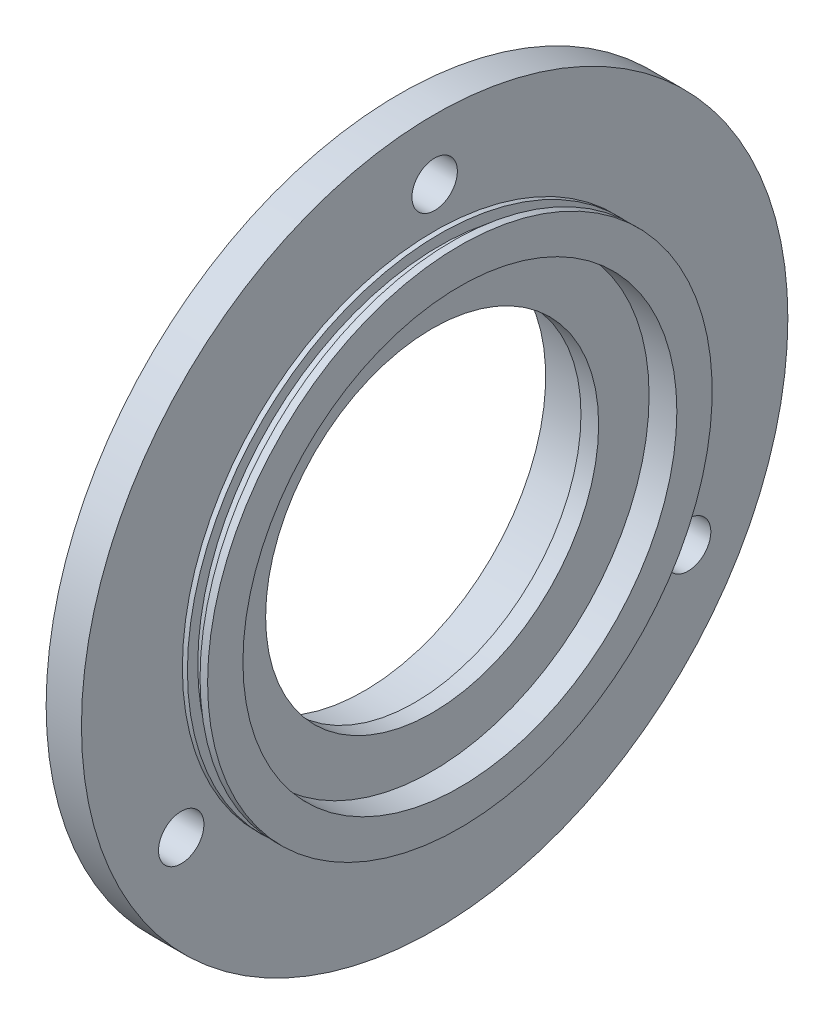
SolidWorks part; units mm, degrees
ref_plane "Piano frontale" through (0, 0, 0) normal (0, 0, 1) x (1, 0, 0)
ref_plane "Piano superiore" through (0, 0, 0) normal (0, 1, 0) x (1, 0, 0)
ref_plane "Piano destro" through (0, 0, 0) normal (1, 0, 0) x (0, 0, -1)
sketch "Schizzo1" plane through (0, 0, 0) normal (0, 0, 1) x (1, 0, 0)
  line L0 (0, 43) -> (0, 50)
  line L1 (0, 50) -> (-1.5, 50)
  line L2 (-5, 50) -> (-5, 70)
  line L3 (-5, 70) -> (-12, 70)
  line L4 (-12, 70) -> (-12, 39)
  line L5 (-12, 39) -> (-19, 39)
  line L10 (-5.5, 33) -> (-5.5, 43)
  line L11 (-5.5, 43) -> (0, 43)
  line L12 (-54.5549, 0) -> (51.5767, 0) construction
  line L13 (-19, 39) -> (-19, 36)
  line L14 (-19, 36) -> (-9, 36)
  line L15 (-9, 36) -> (-9, 33)
  line L16 (-5.5, 33) -> (-9, 33)
  line L17 (-4, 50) -> (-4, 47.95)
  line L18 (-4, 47.95) -> (-1.5, 47.95)
  line L19 (-1.5, 47.95) -> (-1.5, 50)
  line L20 (-4, 50) -> (-5, 50)
  point P19 (-1.5, 48.975)
  dimension "D1" = 43
  dimension "D2" = 5.5
  dimension "D3" = 5
  dimension "D4" = 47.95
  dimension "D5" = 7
  dimension "D6" = 50
  dimension "10" = 7
  dimension "D7" = 70
  dimension "40" = 33
  dimension "D8" = 3.5
  dimension "D9" = 36
  dimension "D10" = 3
  dimension "D11" = 2.5
  dimension "D12" = 1.5
revolve "Rivoluzione1" add sketch "Schizzo1" angle 360 about L12
sketch "Schizzo2" plane through (-12, 0, 0) normal (-1, 0, 0) x (0, 0, 1)
  circle A0 centre (0, 58) radius 4.5
  circle A1 centre (0, 0) radius 39 construction
  circle A2 centre (50.2295, -29) radius 4.5
  circle A3 centre (-50.2295, -29) radius 4.5
  point P11 (0, 0)
  dimension "D1" = 9
  dimension "D2" = 58
extrude "Taglio-Estrusione2" cut sketch "Schizzo2" against normal blind 57
